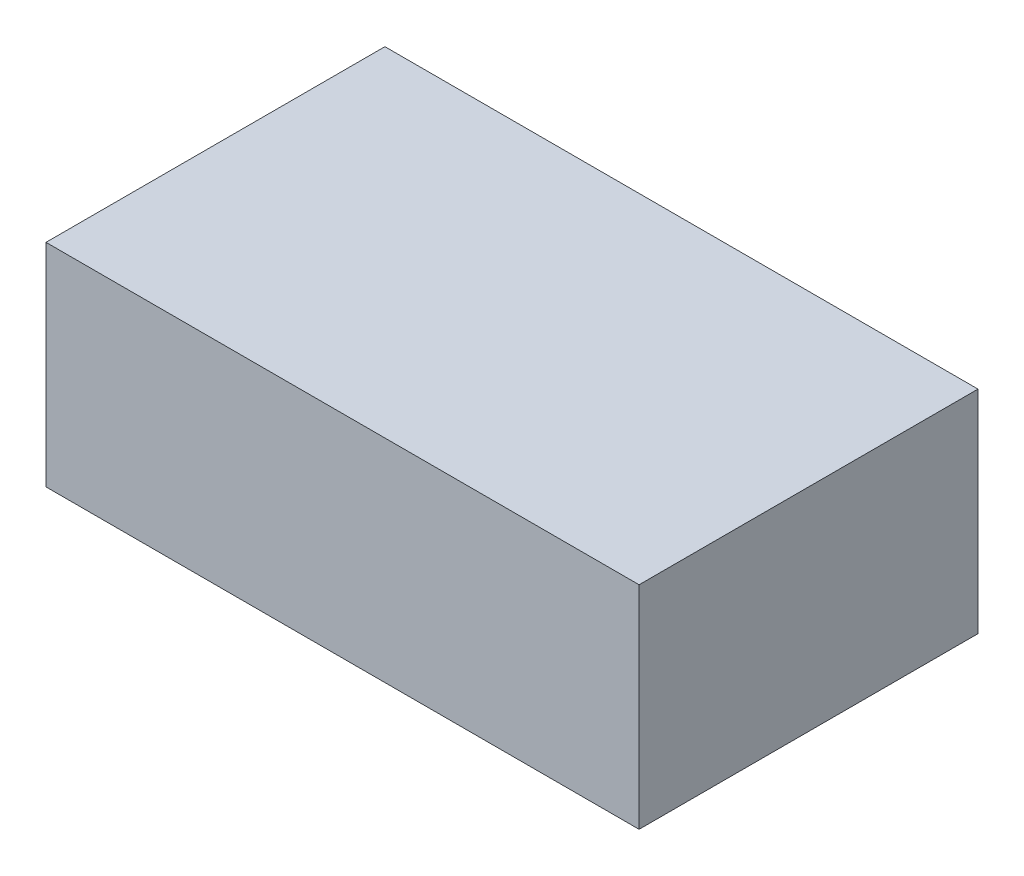
SolidWorks part; units mm, degrees
ref_plane "前视基准面" through (0, 0, 0) normal (0, 0, 1) x (1, 0, 0)
ref_plane "上视基准面" through (0, 0, 0) normal (0, 1, 0) x (1, 0, 0)
ref_plane "右视基准面" through (0, 0, 0) normal (1, 0, 0) x (0, 0, -1)
sketch "草图1" plane through (0, 0, 0) normal (0, 0, 1) x (1, 0, 0)
  line L1 (-99.9327, 30.8923) -> (40.0673, 30.8923)
  line L2 (-99.9327, 30.8923) -> (-99.9327, -19.1077)
  line L3 (-99.9327, -19.1077) -> (40.0673, -19.1077)
  line L4 (40.0673, 30.8923) -> (40.0673, -19.1077)
  dimension "D1" = 50
  dimension "D2" = 140
extrude "凸台-拉伸1" add sketch "草图1" along normal blind 80 contours L1 L4 L3 L2
sketch "草图3" plane through (0, 0, 0) normal (0, 0, -1) x (-1, 0, 0)
  line L0 (99.9327, 30.8923) -> (99.9327, -19.1077) construction
  line L1 (9.9327, 25.8923) -> (49.9327, 25.8923)
  line L2 (9.9327, 25.8923) -> (9.9327, -14.1077)
  line L3 (9.9327, -14.1077) -> (49.9327, -14.1077)
  line L4 (49.9327, 25.8923) -> (49.9327, -14.1077)
  line L5 (-35.0673, 25.8923) -> (4.9327, 25.8923)
  line L6 (-35.0673, 25.8923) -> (-35.0673, -14.1077)
  line L7 (-35.0673, -14.1077) -> (4.9327, -14.1077)
  line L8 (4.9327, 25.8923) -> (4.9327, -14.1077)
  line L9 (54.9327, 25.8923) -> (94.9327, 25.8923)
  line L10 (54.9327, 25.8923) -> (54.9327, -14.1077)
  line L11 (54.9327, -14.1077) -> (94.9327, -14.1077)
  line L12 (94.9327, 25.8923) -> (94.9327, -14.1077)
  line L13 (99.9327, 30.8923) -> (-40.0673, 30.8923) construction
  line L14 (99.9327, 30.8923) -> (-40.0673, 30.8923) construction
  dimension "D1" = 40
  dimension "D2" = 40
  dimension "D3" = 40
  dimension "D4" = 40
  dimension "D5" = 40
  dimension "D6" = 40
  dimension "D7" = 5
  dimension "D8" = 5
  dimension "D9" = 5
  dimension "D10" = 5
  dimension "D11" = 5
  dimension "D12" = 5
extrude "切除-拉伸3" cut sketch "草图3" against normal blind 75
